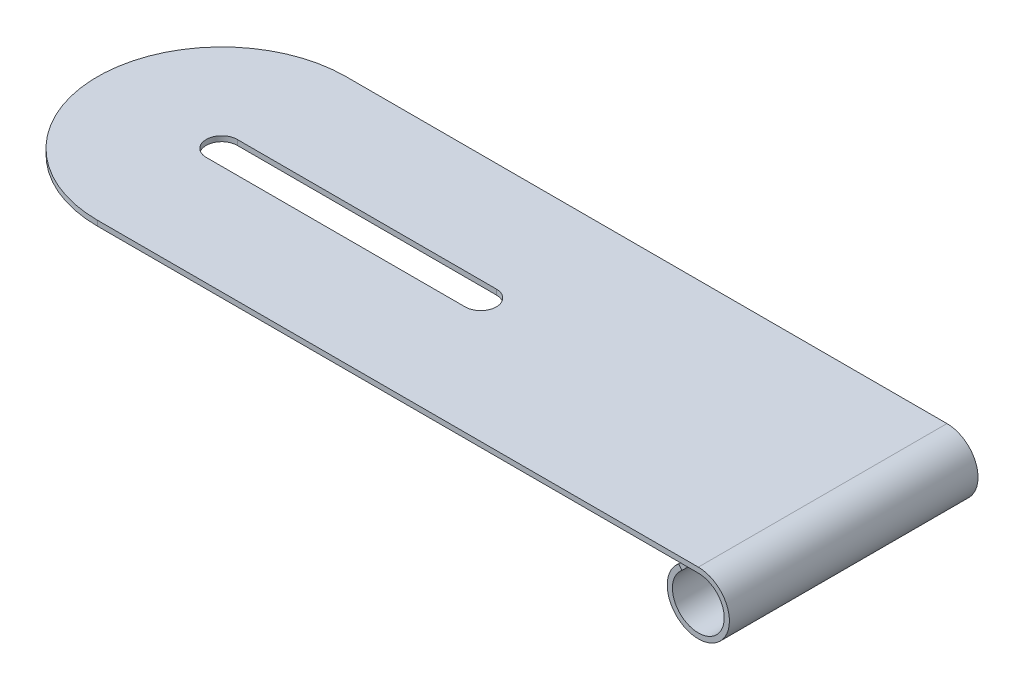
SolidWorks part; units mm, degrees
material "0.6010 (EN-GJL-100)"
ref_plane "Alzado" through (0, 0, 0) normal (0, 0, 1) x (1, 0, 0)
ref_plane "Planta" through (0, 0, 0) normal (0, 1, 0) x (1, 0, 0)
ref_plane "Vista lateral" through (0, 0, 0) normal (1, 0, 0) x (0, 0, -1)
sketch "Croquis1" plane through (0, 0, 0) normal (0, 0, 1) x (1, 0, 0)
  line L0 (0, 3) -> (-70, 3)
  line L1 (0, 2.5) -> (-70, 2.5)
  line L2 (-70, 2.5) -> (-70, 3)
  line L3 (-1.8904, 2.3294) -> (-1.5754, 1.9412)
  arc A0 (-1.5754, 1.9412) -> (0, 2.5) centre (0, 0) ccw
  arc A1 (-1.8904, 2.3294) -> (0, 3) centre (0, 0) ccw
  dimension "D1" = 5
  dimension "D2" = 6
  dimension "D3" = 70
extrude "Saliente-Extruir1" add sketch "Croquis1" along normal blind 24
sketch "Croquis2" plane through (0, 3, 0) normal (0, 1, 0) x (1, 0, 0)
  line L0 (0, 0) -> (-70, 0) construction
  line L1 (0, -24) -> (-70, -24) construction
  line L2 (-70, -24) -> (-70, 0) construction
  line L3 (-58, -10.5) -> (-33, -10.5)
  line L4 (-33, -13.5) -> (-58, -13.5)
  line L5 (-58, 0) -> (-75.7654, 0)
  line L6 (-75.7654, 0) -> (-75.7654, -24)
  line L7 (-75.7654, -24) -> (-58, -24)
  arc A0 (-58, 0) -> (-58, -24) centre (-58, -12) ccw
  arc A1 (-58, -10.5) -> (-58, -13.5) centre (-58, -12) ccw
  arc A2 (-33, -13.5) -> (-33, -10.5) centre (-33, -12) ccw
  point P3 (-70, -12)
  dimension "D1" = 12
  dimension "D2" = 3
extrude "Cortar-Extruir1" cut sketch "Croquis2" against normal blind 1
